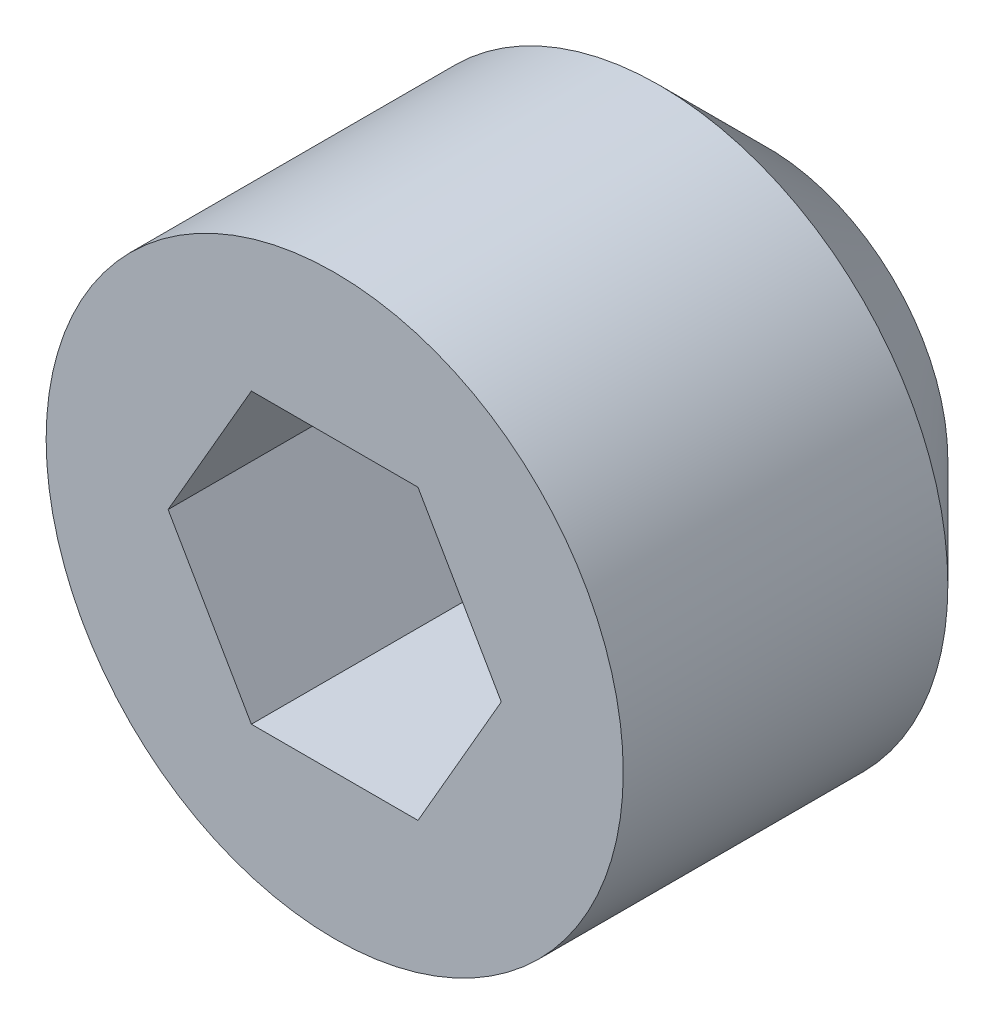
SolidWorks part; units mm, degrees
ref_plane "Front Plane" through (0, 0, 0) normal (0, 0, 1) x (1, 0, 0)
ref_plane "Top Plane" through (0, 0, 0) normal (0, 1, 0) x (1, 0, 0)
ref_plane "Right Plane" through (0, 0, 0) normal (1, 0, 0) x (0, 0, -1)
sketch "Sketch1" plane through (0, 0, 0) normal (0, 0, 1) x (1, 0, 0)
  circle A0 centre (0, 0) radius 2
  dimension "D1" = 4
extrude "Boss-Extrude1" add sketch "Sketch1" against normal blind 3
sketch "Sketch2" plane through (0, 0, 0) normal (0, 0, 1) x (1, 0, 0)
  line L1 (1.1547, 0) -> (0.5774, 1)
  line L2 (0.5774, 1) -> (-0.5774, 1)
  line L3 (-0.5774, 1) -> (-1.1547, 0)
  line L4 (-1.1547, 0) -> (-0.5774, -1)
  line L5 (-0.5774, -1) -> (0.5774, -1)
  line L6 (0.5774, -1) -> (1.1547, 0)
  circle A0 centre (0, 0) radius 1 construction
  dimension "D1" = 2
extrude "Cut-Extrude1" cut sketch "Sketch2" against normal blind 1.5
sketch3d "3DSketch1"
  line L0 (0, 0, 0) -> (0, 0, -3) construction
sketch "Sketch3" plane through (0, 0, 0) normal (1, 0, 0) x (0, 0, -1)
  line L0 (3, 2) -> (3, -2)
  line L1 (3, 2) -> (3, 1.25)
  line L2 (0, 0) -> (3, 0) construction
  line L3 (3, 1.25) -> (2.25, 2)
  line L5 (3, 2) -> (0, 2)
  line L6 (0, -0.8) -> (3, -2)
  line L8 (3, 2) -> (2.25, 2)
  dimension "D1" = 1.25
  dimension "D3" = 45
revolve "Chamfer" cut sketch "Sketch3" angle 360 about L0
sketch "Sketch4" plane through (0, 0, 0) normal (1, 0, 0) x (0, 0, -1)
  line L0 (3, 1.25) -> (3, -1.25)
  line L1 (3, 1.25) -> (3, 0)
  line L2 (3, 0) -> (2.545, 0)
  line L3 (2.545, 0) -> (3, 1.25)
  dimension "D1" = 20
revolve "Hollow" [suppressed] cut sketch "Sketch4" angle 360 about L2
sketch "Sketch5" [suppressed] plane through (0, 0, 0) normal (1, 0, 0) x (0, 0, -1)
  line L0 (0, 0) -> (6, 0) construction
  line L1 (5.25, 0) -> (6, 0) construction
  line L2 (5.25, 2) -> (5.25, 0) construction
  line L3 (6, 1.25) -> (6, -1.25)
  line L4 (6, 0) -> (6, -1.25) construction
  line L5 (5.25, 2) -> (6.25, 2)
  line L6 (6.25, 2) -> (6.25, 0)
  line L7 (6.25, 0) -> (6, 0)
  line L9 (5.25, 2) -> (0, 2)
  line L13 (0, -0.8) -> (1.8, -0.8)
  line L15 (-1, 2) -> (0, 2) construction
  arc A0 (5.25, 2) -> (6, 0) centre (2.9583, 0) cw
  dimension "D1" = 0.25
  dimension "D2" = 1
revolve "Domed" [suppressed] cut sketch "Sketch5" angle 360 about L7
sketch "Sketch6" [suppressed] plane through (0, 0, 0) normal (1, 0, 0) x (0, 0, -1)
  line L0 (6, 1.25) -> (6, -1.25)
  line L1 (6, 1.25) -> (6, 0) construction
  line L3 (5.25, 2) -> (3.25, 2)
  line L6 (5.25, 2) -> (0, 2)
  line L7 (6, 1.25) -> (5.25, 2)
  line L8 (5.25, 2) -> (0, 2) construction
  line L9 (3.25, 2) -> (4, 1.25)
  line L10 (4, 1.25) -> (6, 1.25)
  line L11 (0, -0.8) -> (1.8, -0.8)
  line L12 (0, 2) -> (0, -2) construction
  line L13 (0, 2) -> (-1, 2) construction
  dimension "D1" = 0.5
  dimension "D2" = 1
revolve "Dog" [suppressed] cut sketch "Sketch6" angle 360
